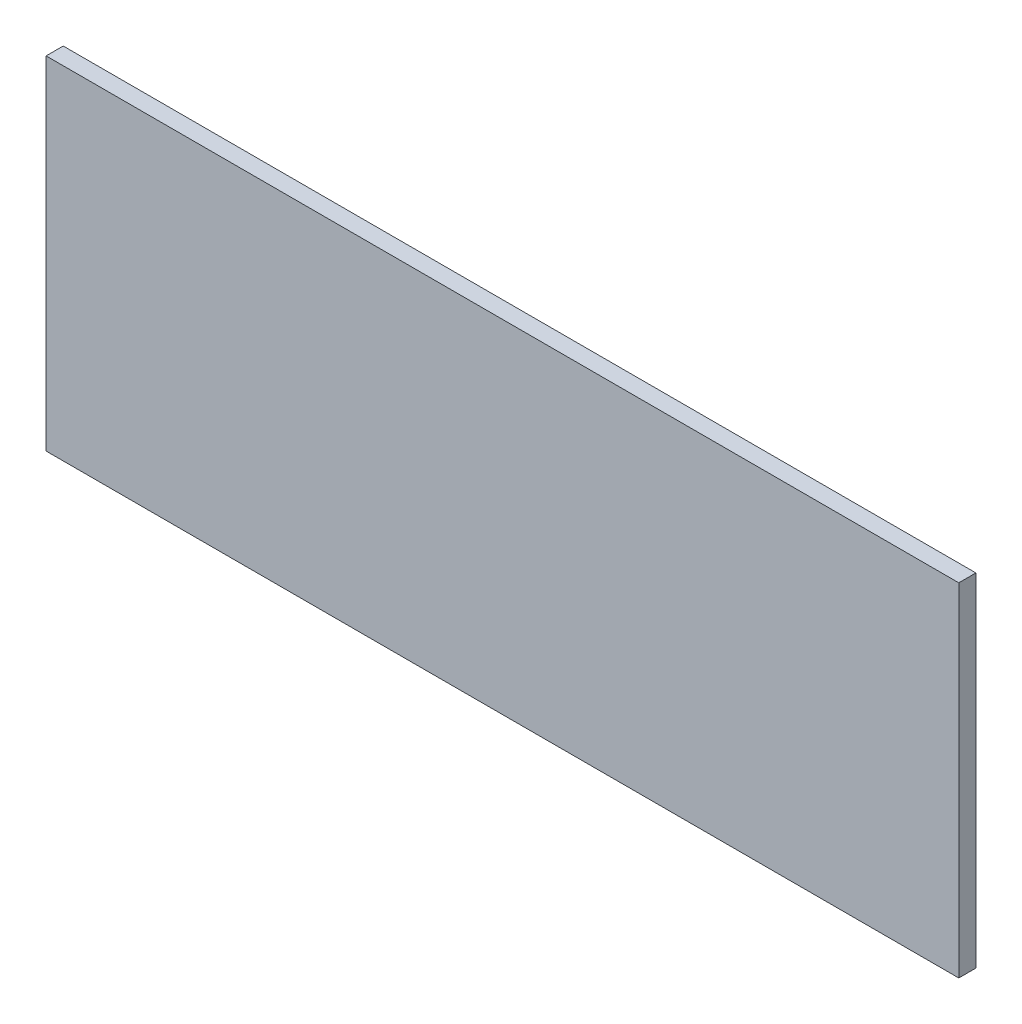
SolidWorks part; units mm, degrees
ref_plane "Plan de face" through (0, 0, 0) normal (0, 0, 1) x (1, 0, 0)
ref_plane "Plan de dessus" through (0, 0, 0) normal (0, 1, 0) x (1, 0, 0)
ref_plane "Plan de droite" through (0, 0, 0) normal (1, 0, 0) x (0, 0, -1)
sketch "Esquisse1" plane through (0, 0, 0) normal (0, 0, 1) x (1, 0, 0)
  line L1 (-160, -60) -> (160, -60)
  line L2 (-160, -60) -> (-160, 60)
  line L3 (-160, 60) -> (160, 60)
  line L4 (160, -60) -> (160, 60)
  line L5 (-160, -60) -> (160, 60) construction
  line L6 (-160, 60) -> (160, -60) construction
  point P0 (0, 0)
  dimension "D1" = 320
  dimension "D2" = 120
extrude "Boss.-Extru.1" add sketch "Esquisse1" along normal blind 6
